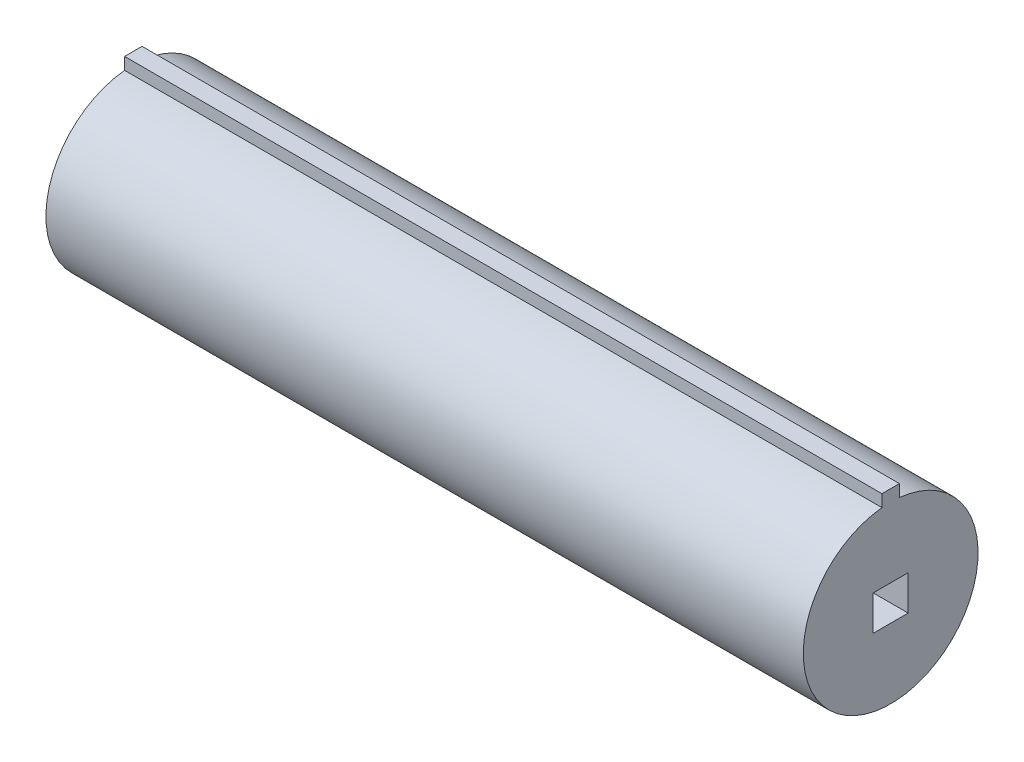
SolidWorks part; units mm, degrees
ref_plane "前视基准面" through (0, 0, 0) normal (0, 0, 1) x (1, 0, 0)
ref_plane "上视基准面" through (0, 0, 0) normal (0, 1, 0) x (1, 0, 0)
ref_plane "右视基准面" through (0, 0, 0) normal (1, 0, 0) x (0, 0, -1)
other "Configuration Table"
sketch "草图1" plane through (0, 0, 0) normal (1, 0, 0) x (0, 0, -1)
  line L1 (-1.5, 0) -> (1.5, 0)
  line L2 (-1.5, 0) -> (-1.5, 17)
  line L3 (-1.5, 17) -> (1.5, 17)
  line L4 (1.5, 0) -> (1.5, 17)
  circle A0 centre (0, 0) radius 15
  point P7 (0, 0)
  dimension "D1" = 30
  dimension "D2" = 3
  dimension "D3" = 17
extrude "凸台-拉伸1" add sketch "草图1" along normal blind 130 from offset 0 contours L2 A0 L4 L1 | A0 L4 L3 L2 | L4 A0 L2 L1
sketch "草图2" plane through (130, 0, 0) normal (1, 0, 0) x (0, 0, -1)
  line L1 (-3, -3) -> (3, -3)
  line L2 (-3, -3) -> (-3, 3)
  line L3 (-3, 3) -> (3, 3)
  line L4 (3, -3) -> (3, 3)
  line L5 (-3, -3) -> (3, 3) construction
  line L6 (-3, 3) -> (3, -3) construction
  point P0 (0, 0)
  dimension "D1" = 6
  dimension "D2" = 6
extrude "切除-拉伸1" cut sketch "草图2" against normal blind 15
